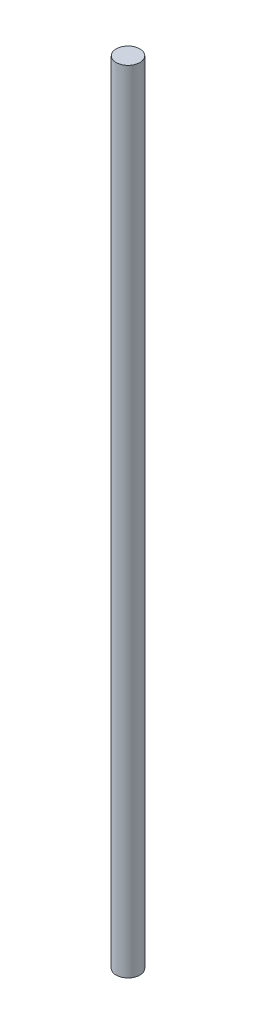
SolidWorks part; units mm, degrees
other "Frame Tie Stud"
ref_plane "Front Plane" through (0, 0, 0) normal (0, 0, 1) x (1, 0, 0)
ref_plane "Top Plane" through (0, 0, 0) normal (0, 1, 0) x (1, 0, 0)
ref_plane "Right Plane" through (0, 0, 0) normal (1, 0, 0) x (0, 0, -1)
sketch3d "Base Outline Sketch datum points"
  point P0 (0, -165.1, 0)
  point P1 (10, -165.1, 0)
  point P2 (0, -165.1, -10)
ref_plane "Base Outline Sketch plane" through (0, -165.1, 0) normal (0, 1, 0) x (1, 0, 0)
sketch "Base Outline Sketch" plane through (0, -165.1, 0) normal (0, 1, 0) x (1, 0, 0)
  circle A0 centre (-56.2917, -50) radius 1.5
extrude "Base Outline" add sketch "Base Outline Sketch" along normal blind 100 separate body
